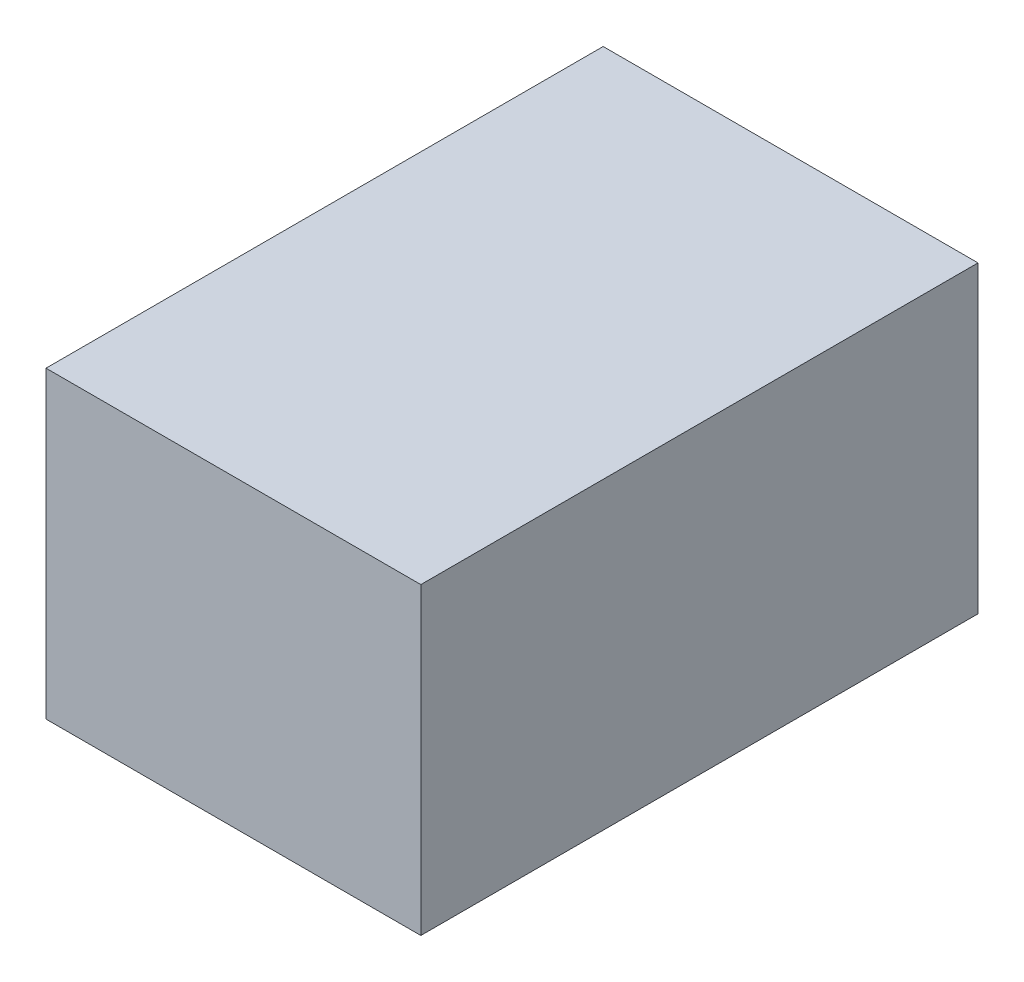
SolidWorks part; units mm, degrees
material "Plastique personnalisé"
ref_plane "Plan de face" through (0, 0, 0) normal (0, 0, 1) x (1, 0, 0)
ref_plane "Plan de dessus" through (0, 0, 0) normal (0, 1, 0) x (1, 0, 0)
ref_plane "Plan de droite" through (0, 0, 0) normal (1, 0, 0) x (0, 0, -1)
sketch "Esquisse1" plane through (0, 0, 0) normal (0, 1, 0) x (1, 0, 0)
  line L1 (0, 0) -> (37, 0)
  line L2 (0, 0) -> (0, 55)
  line L3 (0, 55) -> (37, 55)
  line L4 (37, 0) -> (37, 55)
  dimension "D1" = 37
  dimension "D2" = 55
extrude "Boss.-Extru.1" add sketch "Esquisse1" along normal blind 30 contours L3 L4 L1 L2
ref_plane "Plan1" through (0, 0, 0) normal (-1, 0, 0) x (0, 0, 1)
ref_plane "Plan2" through (0, 0, 0) normal (0, -1, 0) x (-1, 0, 0)
